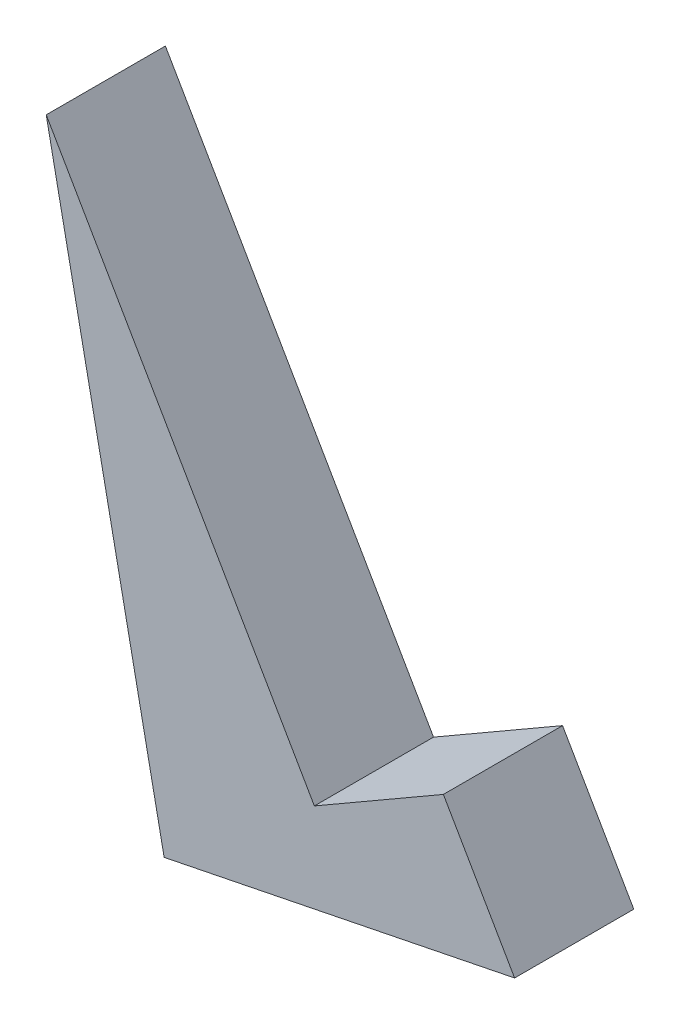
SolidWorks part; units mm, degrees
ref_plane "Plan de face" through (0, 0, 0) normal (0, 0, 1) x (1, 0, 0)
ref_plane "Plan de dessus" through (0, 0, 0) normal (0, 1, 0) x (1, 0, 0)
ref_plane "Plan de droite" through (0, 0, 0) normal (1, 0, 0) x (0, 0, -1)
sketch "Model" plane through (0, 0, 0) normal (0, 0, 1) x (1, 0, 0)
  line L43 (422.702, -113.8466) -> (411.8767, -120.0966)
  line L44 (411.8767, -120.0966) -> (389.3767, -81.1254)
  line L46 (389.3767, -81.1254) -> (399.2724, -130.1364)
  line L47 (399.2724, -130.1364) -> (428.679, -124.199)
  line L49 (428.679, -124.199) -> (422.702, -113.8466)
  dimension "D1" = 45
  dimension "D2" = 50
  dimension "D3" = 30
  dimension "D4" = 12.5
extrude "Boss.-Extru.1" add sketch "Model" along normal blind 10
